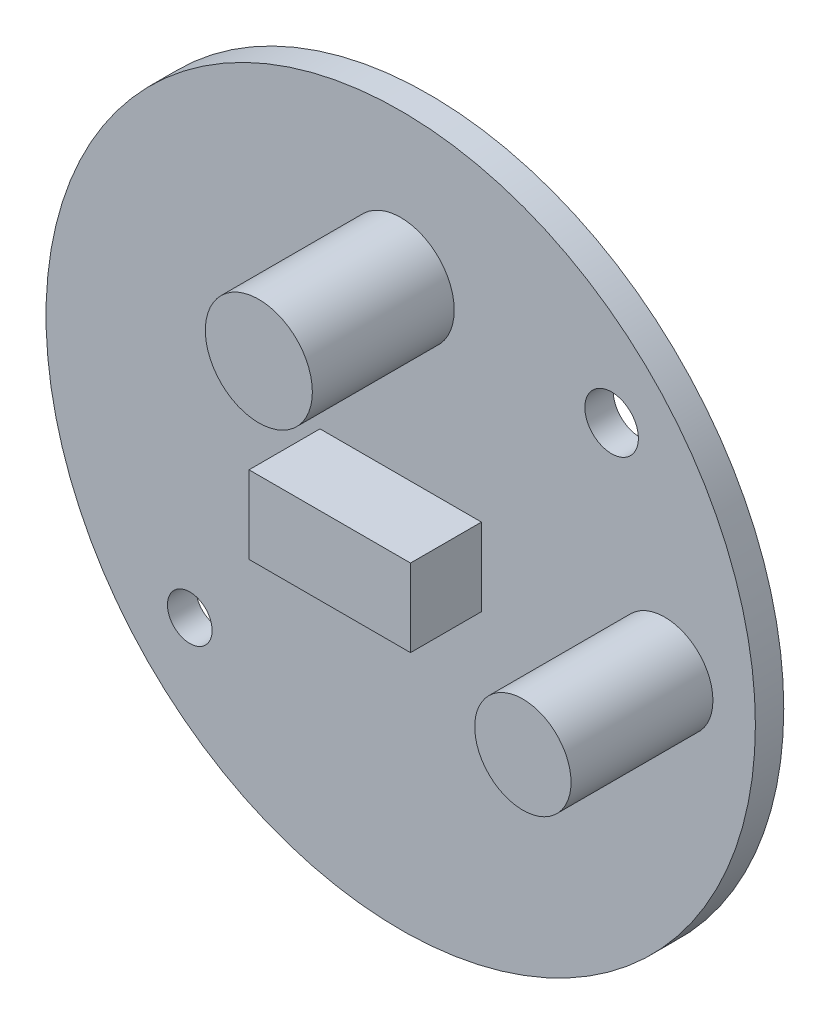
SolidWorks part; units mm, degrees
ref_plane "Front Plane" through (0, 0, 0) normal (0, 0, 1) x (1, 0, 0)
ref_plane "Top Plane" through (0, 0, 0) normal (0, 1, 0) x (1, 0, 0)
ref_plane "Right Plane" through (0, 0, 0) normal (1, 0, 0) x (0, 0, -1)
sketch "Sketch1" plane through (0, 0, 0) normal (0, 0, 1) x (1, 0, 0)
  circle A0 centre (0, 0) radius 25
  dimension "D1" = 50
extrude "Boss-Extrude1" add sketch "Sketch1" along normal blind 2
sketch "Sketch2" plane through (0, 0, 2) normal (0, 0, 1) x (1, 0, 0)
  circle A0 centre (0, 14.7127) radius 3.7725
  circle A1 centre (18.6111, 0) radius 3.3952
extrude "Boss-Extrude2" add sketch "Sketch2" along normal blind 10
sketch "Sketch3" plane through (0, 0, 2) normal (0, 0, 1) x (1, 0, 0)
  line L1 (-5.6904, 2.735) -> (5.6904, 2.735)
  line L2 (-5.6904, 2.735) -> (-5.6904, -2.735)
  line L3 (-5.6904, -2.735) -> (5.6904, -2.735)
  line L4 (5.6904, 2.735) -> (5.6904, -2.735)
  line L5 (-5.6904, 2.735) -> (5.6904, -2.735) construction
  line L6 (-5.6904, -2.735) -> (5.6904, 2.735) construction
  point P0 (0, 0)
extrude "Boss-Extrude3" add sketch "Sketch3" along normal blind 5
sketch "Sketch4" plane through (0, 0, 2) normal (0, 0, 1) x (1, 0, 0)
  line L0 (-14.8659, -13.3793) -> (14.8659, 13.3793) construction
  circle A0 centre (-14.8659, -13.3793) radius 1.5749
  circle A1 centre (14.8659, 13.3793) radius 1.888
  dimension "D1" = 20
extrude "Cut-Extrude1" cut sketch "Sketch4" against normal blind 5
